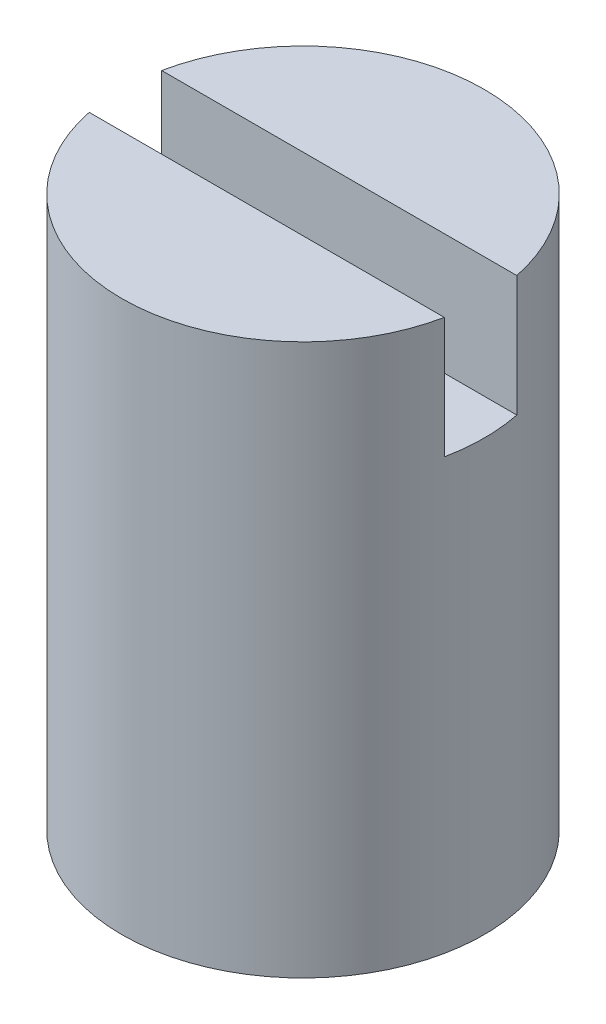
SolidWorks part; units mm, degrees
material "6061-T6 (SS)"
ref_plane "X-Y Datum" through (0, 0, 0) normal (0, 0, 1) x (1, 0, 0)
ref_plane "X-Z Datum" through (0, 0, 0) normal (0, 1, 0) x (1, 0, 0)
ref_plane "Y-Z Datum" through (0, 0, 0) normal (1, 0, 0) x (0, 0, -1)
sketch "Sketch1" plane through (0, 0, 0) normal (0, 1, 0) x (1, 0, 0)
  circle A0 centre (0, 0) radius 4.7625
  dimension "D1" = 9.525
extrude "Boss-Extrude1" add sketch "Sketch1" against normal blind 14.478
sketch "Sketch2" plane through (0, 0, 0) normal (0, 1, 0) x (1, 0, 0)
  line L5 (4.7625, 0.9525) -> (-4.7625, 0.9525)
  line L6 (4.7625, 0.9525) -> (4.7625, -0.9525)
  line L7 (4.7625, -0.9525) -> (-4.7625, -0.9525)
  line L8 (-4.7625, 0.9525) -> (-4.7625, -0.9525)
  line L9 (4.7625, 0.9525) -> (-4.7625, -0.9525) construction
  line L10 (4.7625, -0.9525) -> (-4.7625, 0.9525) construction
  point P0 (0, 0)
  dimension "D1" = 9.525
  dimension "D2" = 1.905
extrude "Cut-Extrude1" cut sketch "Sketch2" against normal blind 3.175
sketch "Sketch3" plane through (0, -14.478, 0) normal (0, -1, 0) x (1, 0, 0)
  circle A0 centre (0, 0) radius 2
  dimension "D1" = 4
extrude "Cut-Extrude2" cut sketch "Sketch3" against normal blind 5
